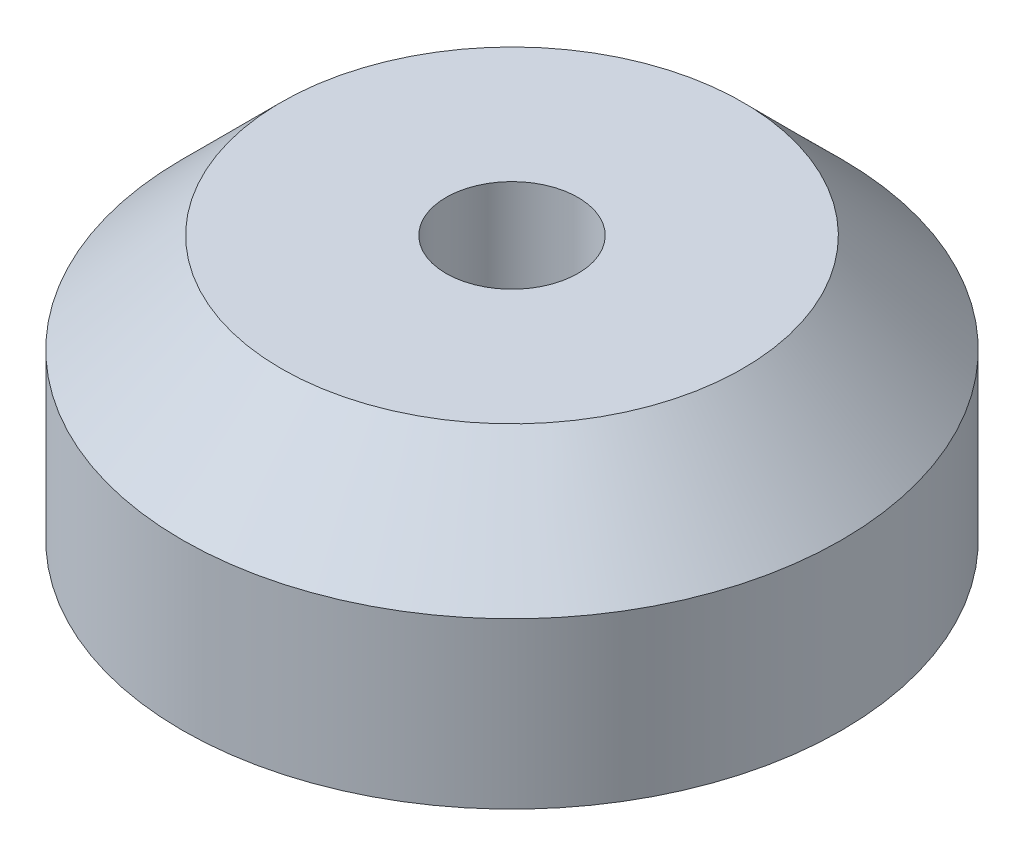
SolidWorks part; units mm, degrees
material "Fundición gris"
ref_plane "Alzado" through (0, 0, 0) normal (0, 0, 1) x (1, 0, 0)
ref_plane "Planta" through (0, 0, 0) normal (0, 1, 0) x (1, 0, 0)
ref_plane "Vista lateral" through (0, 0, 0) normal (1, 0, 0) x (0, 0, -1)
sketch "Croquis1" plane through (0, 0, 0) normal (0, 1, 0) x (1, 0, 0)
  circle A0 centre (0, 0) radius 50
  circle A1 centre (0, 0) radius 10
  dimension "D1" = 100
  dimension "D2" = 20
extrude "Saliente-Extruir1" add sketch "Croquis1" along normal blind 40
chamfer "Chaflán1" distance 15 angle 45 1 edges at (0, 40, 50)
shell "Vaciado1" thickness 3
